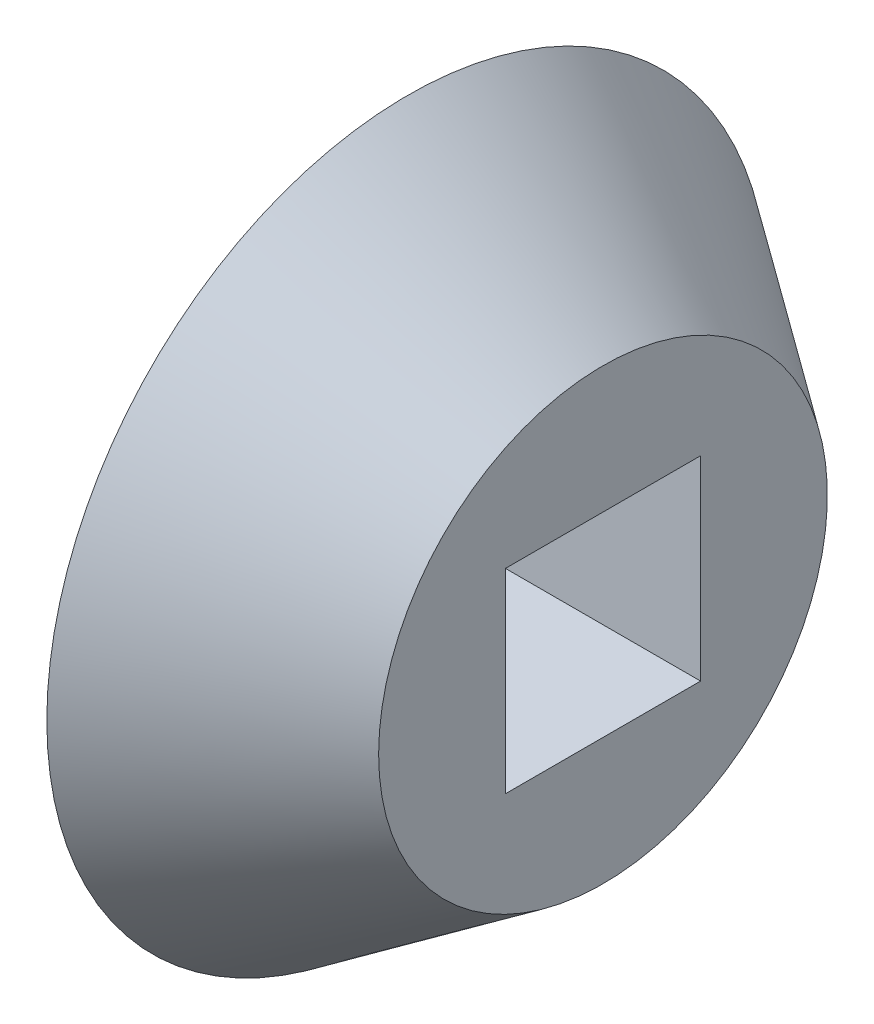
SolidWorks part; units mm, degrees
material "Custom Plastic"
ref_plane "Front Plane" through (0, 0, 0) normal (0, 0, 1) x (1, 0, 0)
ref_plane "Top Plane" through (0, 0, 0) normal (0, 1, 0) x (1, 0, 0)
ref_plane "Right Plane" through (0, 0, 0) normal (1, 0, 0) x (0, 0, -1)
sketch "Sketch1" plane through (0, 0, 0) normal (1, 0, 0) x (0, 0, -1)
  line L1 (1.5875, -1.5875) -> (-1.5875, -1.5875)
  line L2 (1.5875, -1.5875) -> (1.5875, 1.5875)
  line L3 (1.5875, 1.5875) -> (-1.5875, 1.5875)
  line L4 (-1.5875, -1.5875) -> (-1.5875, 1.5875)
  line L5 (1.5875, -1.5875) -> (-1.5875, 1.5875) construction
  line L6 (1.5875, 1.5875) -> (-1.5875, -1.5875) construction
  circle A0 centre (0, 0) radius 5.8738
  dimension "D2" = 11.7475
  dimension "D1" = 3.175
extrude "Boss-Extrude1" add sketch "Sketch1" along normal blind 3.175
sketch "Sketch2" plane through (0, 0, 0) normal (0, 0, 1) x (1, 0, 0)
  line L0 (0, 5.8738) -> (3.175, 5.8738)
  line L1 (0, 5.8738) -> (0, -5.8738) construction
  line L2 (3.175, 5.8738) -> (0, 5.8738) construction
  line L3 (3.175, -5.8738) -> (3.175, 5.8738) construction
  line L4 (3.175, 5.8738) -> (3.175, 3.6506)
  line L5 (3.175, 3.6506) -> (0, 5.8738)
  line L6 (0, 0) -> (3.175, 0) construction
  dimension "D1" = 35
revolve "Cut-Revolve1" cut sketch "Sketch2" angle 360 about L6
